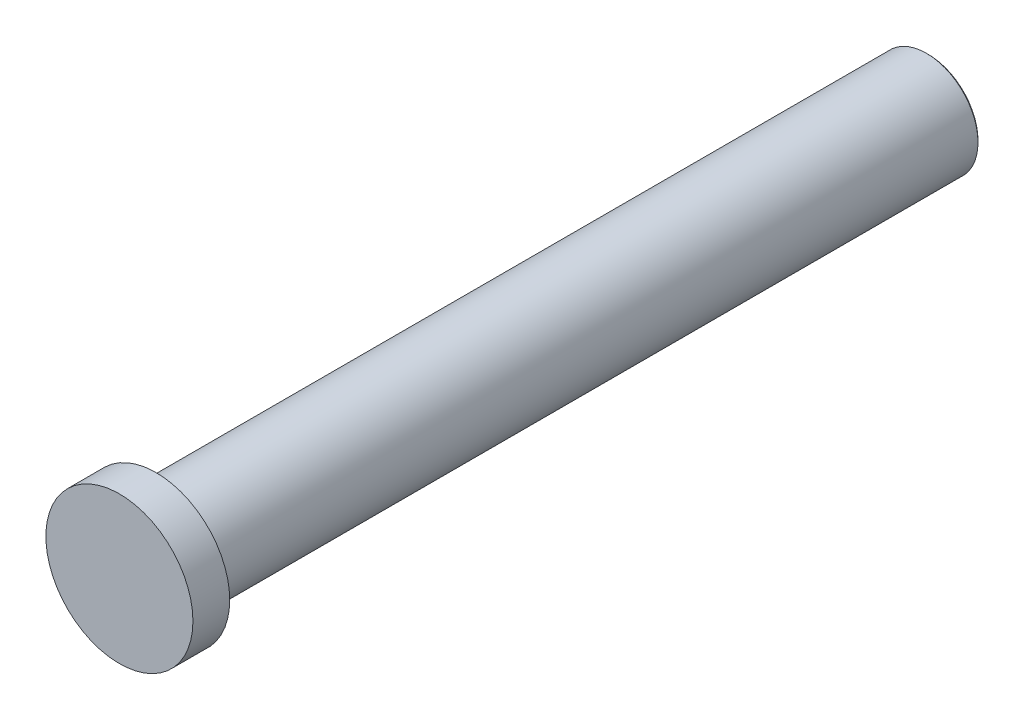
SolidWorks part; units mm, degrees
ref_plane "Front Plane" through (0, 0, 0) normal (0, 0, 1) x (1, 0, 0)
ref_plane "Top Plane" through (0, 0, 0) normal (0, 1, 0) x (1, 0, 0)
ref_plane "Right Plane" through (0, 0, 0) normal (1, 0, 0) x (0, 0, -1)
sketch "Sketch2" plane through (0, 0, 0) normal (0, 0, 1) x (1, 0, 0)
  circle A0 centre (0, 0) radius 1.4
  dimension "D1" = 2.8
extrude "Boss-Extrude1" add sketch "Sketch2" along normal blind 21
chamfer "Chamfer2" distance 0.05 angle 45 2 edges at (1.4, 0, 21) (1.4, 0, 0)
sketch "Sketch3" plane through (0, 0, 21) normal (0, 0, 1) x (1, 0, 0)
  circle A0 centre (0, 0) radius 2
  dimension "D1" = 4
extrude "Boss-Extrude2" add sketch "Sketch3" along normal blind 1
